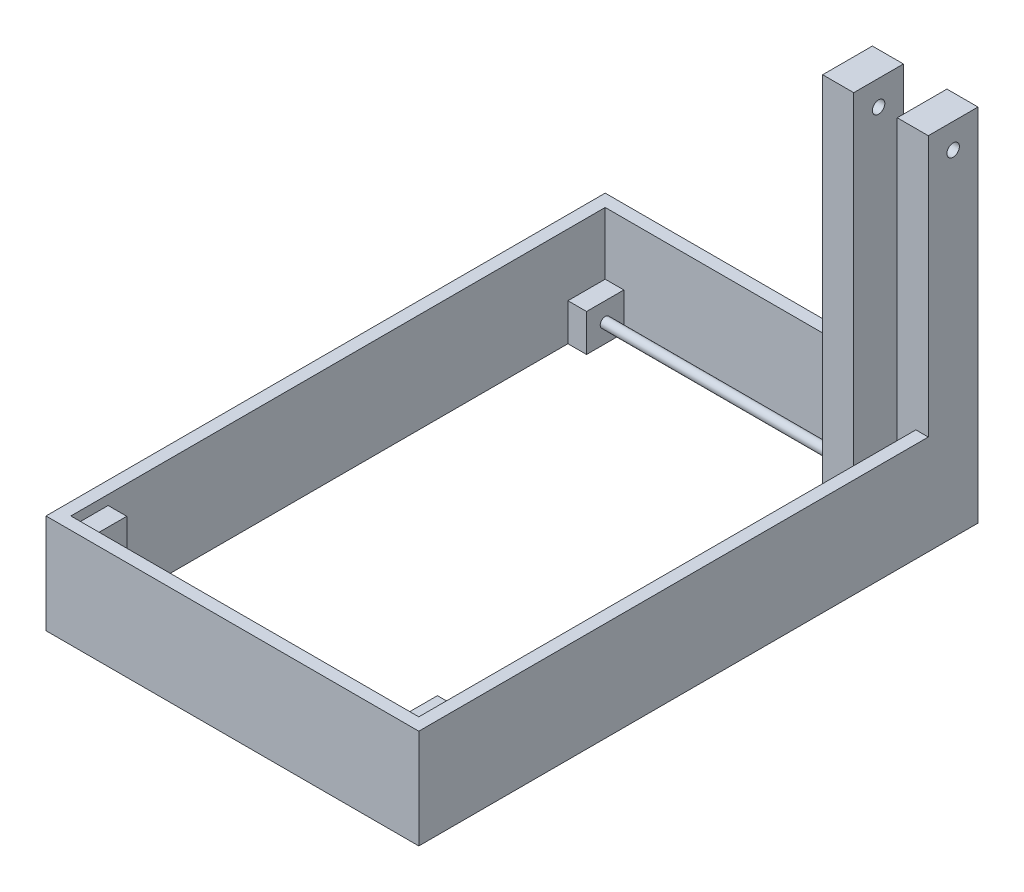
SolidWorks part; units mm, degrees
other "Markup1"
sketch "Sketch11" plane through (-174, 270, 225) normal (-0.1425, 0.7139, 0.6856) x (0.9887, 0.1347, 0.0652)
ref_plane "Front Plane" through (0, 0, 0) normal (0, 0, 1) x (1, 0, 0)
ref_plane "Top Plane" through (0, 0, 0) normal (0, 1, 0) x (1, 0, 0)
ref_plane "Right Plane" through (0, 0, 0) normal (1, 0, 0) x (0, 0, -1)
sketch "Sketch1" plane through (0, 0, 0) normal (0, 1, 0) x (1, 0, 0)
  line L1 (-150, 225) -> (150, 225)
  line L2 (-150, 225) -> (-150, -225)
  line L3 (-150, -225) -> (150, -225)
  line L4 (150, 225) -> (150, -225)
  dimension "D1" = 300
  dimension "D2" = 450
  dimension "D3" = 150
  dimension "D4" = 225
extrude "Boss-Extrude1" add sketch "Sketch1" along normal blind 80
shell "Shell1" thickness 10
sketch "Sketch2" plane through (140, 0, 0) normal (-1, 0, 0) x (0, 0, 1)
  line L0 (-215, 80) -> (-215, 0) construction
  line L1 (-215, 30) -> (-185, 30)
  line L2 (-215, 30) -> (-215, 0)
  line L3 (-215, 0) -> (-185, 0)
  line L4 (-185, 30) -> (-185, 0)
  line L5 (215, 0) -> (-215, 0) construction
  line L6 (-200, 30) -> (-200, 1.2951)
  line L7 (-215, 15) -> (-185, 15)
  line L9 (185, 72.2743) -> (215, 72.2743)
  line L10 (185, 72.2743) -> (185, 42.2743)
  line L11 (185, 42.2743) -> (215, 42.2743)
  line L12 (215, 72.2743) -> (215, 42.2743)
  line L13 (185, 72.2743) -> (215, 42.2743) construction
  line L14 (185, 42.2743) -> (215, 72.2743) construction
  point P12 (200, 57.2743)
  point P17 (-200, 15.6475)
  dimension "D1" = 30
  dimension "D2" = 30
  dimension "D3" = 30
  dimension "D4" = 30
  dimension "D5" = 400
extrude "Boss-Extrude2" add sketch "Sketch2" along normal blind 15
mirror "Mirror2" about plane through (0, 0, 0) normal (1, 0, 0) of "Boss-Extrude2"
sketch "Sketch3" plane through (125, 0, 0) normal (-1, 0, 0) x (0, 0, 1)
  line L1 (-215, 30) -> (-185, 30)
  line L2 (-215, 30) -> (-215, 0)
  line L3 (-215, 0) -> (-185, 0)
  line L4 (-185, 0) -> (-185, 30)
  line L5 (-185, 30) -> (-215, 30)
  line L6 (-215, 30) -> (-215, 0)
  line L7 (-215, 0) -> (-185, 0)
  line L8 (-185, 0) -> (-185, 30)
  line L9 (-185, 30) -> (-215, 30)
  line L10 (-215, 30) -> (-215, 0)
  line L11 (-215, 0) -> (-185, 0)
  line L12 (-185, 30) -> (-185, 0)
  circle A0 centre (-200, 15) radius 4
  dimension "D2" = 8
  dimension "D3" = 15
  dimension "D4" = 15
  dimension "D1" = 0
extrude "Boss-Extrude4" add sketch "Sketch3" along normal up to surface (250 mm away) contours A0
sketch "Sketch4" plane through (125, 0, 0) normal (-1, 0, 0) x (0, 0, 1)
  line L1 (185, 72.2743) -> (215, 72.2743)
  line L2 (185, 72.2743) -> (185, 42.2743)
  line L3 (185, 42.2743) -> (215, 42.2743)
  line L4 (185, 72.2743) -> (185, 42.2743)
  line L5 (185, 42.2743) -> (215, 42.2743)
  line L6 (215, 42.2743) -> (215, 72.2743)
  line L7 (215, 72.2743) -> (185, 72.2743)
  line L8 (185, 72.2743) -> (185, 42.2743)
  line L9 (185, 42.2743) -> (215, 42.2743)
  line L10 (215, 42.2743) -> (215, 72.2743)
  line L11 (215, 72.2743) -> (185, 72.2743)
  line L12 (215, 72.2743) -> (215, 42.2743)
  circle A0 centre (200, 57.2743) radius 4
  dimension "D2" = 8
  dimension "D1" = 0
extrude "Boss-Extrude5" add sketch "Sketch4" along direction (1, 0, 0) on the side of the normal up to surface (250 mm away) contours A0
sketch "Sketch5" plane through (0, 80, 0) normal (0, 1, 0) x (1, 0, 0)
  line L0 (125, 215) -> (125, 185) construction
  line L1 (125, 215) -> (125, 185)
  line L2 (150, -225) -> (150, 225) construction
  line L3 (125, 185) -> (150, 185)
  line L4 (125, 185) -> (125, 225)
  line L5 (125, 225) -> (150, 225)
  line L6 (150, 185) -> (150, 225)
  line L7 (150, 225) -> (-150, 225) construction
extrude "Boss-Extrude6" add sketch "Sketch5" along normal blind 210 and the other way up to surface (80 mm away) contours L4 L3 L6 L5
sketch "Sketch6" plane through (0, 0, -215) normal (0, 0, 1) x (1, 0, 0)
  line L1 (125, 80) -> (90, 80)
  line L2 (125, 80) -> (125, 0)
  line L3 (125, 0) -> (90, 0)
  line L4 (90, 80) -> (90, 0)
  line L6 (125, 0) -> (125, 80)
  line L7 (125, 80) -> (-140, 80)
  line L8 (-140, 80) -> (-140, 30)
  line L9 (-140, 30) -> (-125, 30)
  line L10 (-125, 30) -> (-125, 0)
  line L11 (-125, 0) -> (125, 0)
  line L12 (125, 0) -> (125, 80)
  line L13 (125, 80) -> (-140, 80)
  line L14 (-140, 80) -> (-140, 30)
  line L15 (-140, 30) -> (-125, 30)
  line L16 (-125, 30) -> (-125, 0)
  line L17 (-125, 0) -> (125, 0)
  line M7 (125, 0) -> (125, 80)
  line M8 (125, 80) -> (-140, 80)
  line M12 (-125, 0) -> (125, 0)
  dimension "D2" = 35
  dimension "D1" = 0
extrude "Cut-Extrude1" cut sketch "Sketch6" against normal blind 300 contours L4 M8 M12 M7
sketch "Sketch8" plane through (0, 80, 0) normal (0, 1, 0) x (1, 0, 0)
  line L1 (90, 225) -> (65, 225)
  line L2 (90, 225) -> (90, 185)
  line L3 (90, 185) -> (65, 185)
  line L4 (65, 225) -> (65, 185)
  dimension "D1" = 25
  dimension "D2" = 40
extrude "Boss-Extrude7" add sketch "Sketch8" along normal blind 210 and the other way up to surface
sketch "Sketch10" plane through (125, 0, 0) normal (-1, 0, 0) x (0, 0, 1)
  line L0 (-225, 0) -> (-185, 0) construction
  line L1 (-225, 0) -> (-225, 290) construction
  circle A0 centre (-205, 270) radius 5
  dimension "D3" = 10
  dimension "D1" = 270
  dimension "D2" = 20
extrude "Cut-Extrude2" cut sketch "Sketch10" along normal up to surface and the other way blind 300 up to face at (65, 15, -196)
